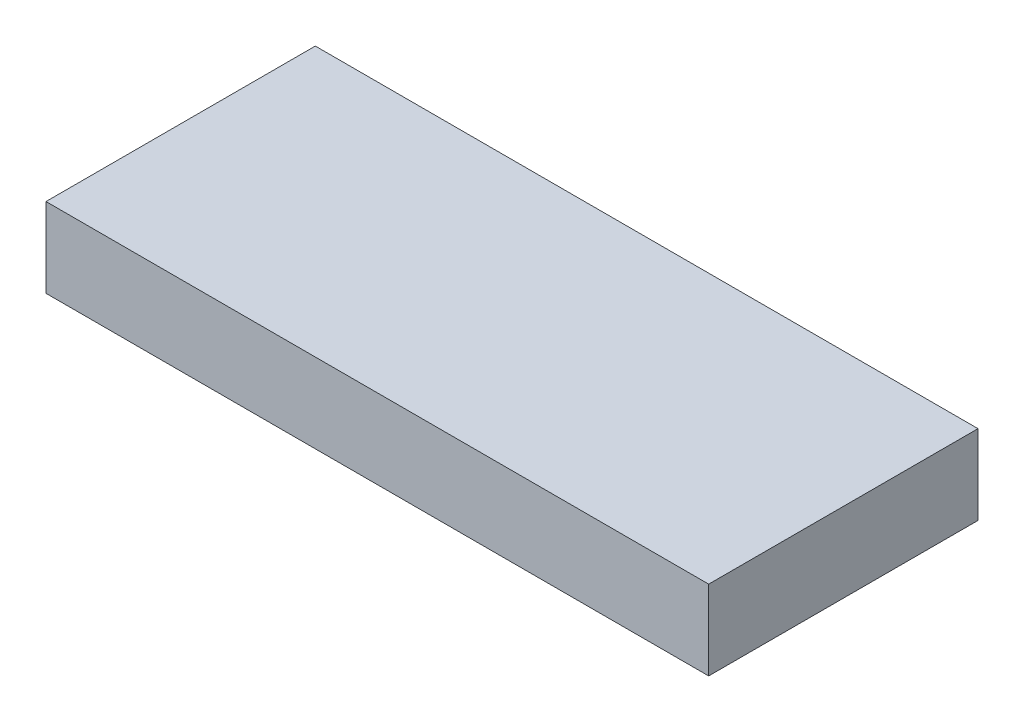
SolidWorks part; units mm, degrees
ref_plane "Front Plane" through (0, 0, 0) normal (0, 0, 1) x (1, 0, 0)
ref_plane "Top Plane" through (0, 0, 0) normal (0, 1, 0) x (1, 0, 0)
ref_plane "Right Plane" through (0, 0, 0) normal (1, 0, 0) x (0, 0, -1)
sketch "Sketch2" plane through (0, 0, 0) normal (0, 1, 0) x (1, 0, 0)
  line L1 (-31.25, -12.7) -> (31.25, -12.7)
  line L2 (-31.25, -12.7) -> (-31.25, 12.7)
  line L3 (-31.25, 12.7) -> (31.25, 12.7)
  line L4 (31.25, -12.7) -> (31.25, 12.7)
  line L5 (-31.25, -12.7) -> (31.25, 12.7) construction
  line L6 (-31.25, 12.7) -> (31.25, -12.7) construction
  point P0 (0, 0)
  dimension "D1" = 62.5
  dimension "D2" = 25.4
extrude "Boss-Extrude1" add sketch "Sketch2" along normal blind 7.5
